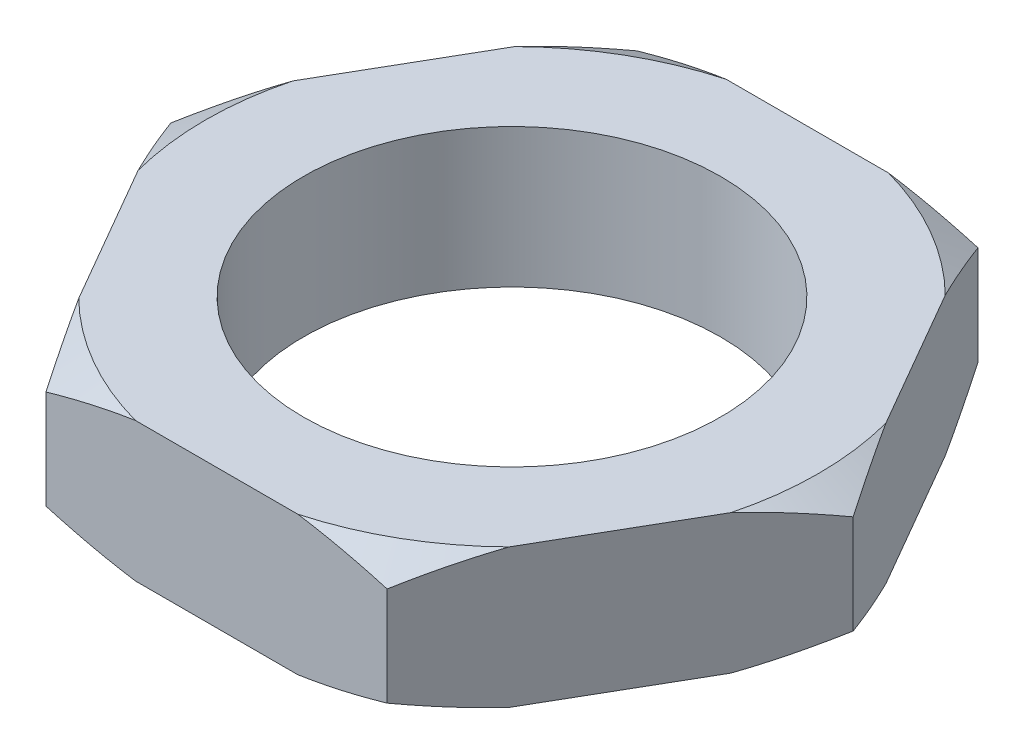
SolidWorks part; units mm, degrees
ref_plane "Front Plane" through (0, 0, 0) normal (0, 0, 1) x (1, 0, 0)
ref_plane "Top Plane" through (0, 0, 0) normal (0, 1, 0) x (1, 0, 0)
ref_plane "Right Plane" through (0, 0, 0) normal (1, 0, 0) x (0, 0, -1)
sketch "Sketch1" plane through (0, 0, 0) normal (0, 1, 0) x (1, 0, 0)
  line L1 (9.815, 0) -> (4.9075, 8.5)
  line L2 (4.9075, 8.5) -> (-4.9075, 8.5)
  line L3 (-4.9075, 8.5) -> (-9.815, 0)
  line L4 (-9.815, 0) -> (-4.9075, -8.5)
  line L5 (-4.9075, -8.5) -> (4.9075, -8.5)
  line L6 (4.9075, -8.5) -> (9.815, 0)
  circle A0 centre (0, 0) radius 8.5 construction
  circle A1 centre (0, 0) radius 6
  dimension "D2" = 12
  dimension "D1" = 17
extrude "Boss-Extrude1" add sketch "Sketch1" along normal blind 4
sketch "Sketch2" plane through (0, 0, 0) normal (0, 0, 1) x (1, 0, 0)
  line L0 (-9.815, 3.4226) -> (-8.815, 4)
  line L1 (-9.815, 4) -> (-9.815, 0) construction
  line L2 (-9.815, 4) -> (-4.9075, 4) construction
  line L3 (-8.815, 4) -> (-9.815, 4)
  line L4 (-9.815, 4) -> (-9.815, 3.4226)
  line L5 (-9.815, 2) -> (-7.9667, 2) construction
  line L6 (-9.815, 0) -> (-9.815, 0.5774)
  line L8 (-8.815, 0) -> (-9.815, 0)
  line L9 (-9.815, 0.5774) -> (-8.815, 0)
  line L10 (0, 0) -> (0, 6.4027) construction
  line L11 (-4.9075, 0) -> (4.9075, 0) construction
  dimension "D1" = 30
  dimension "D2" = 1
revolve "Cut-Revolve1" cut sketch "Sketch2" angle 360 about L10
